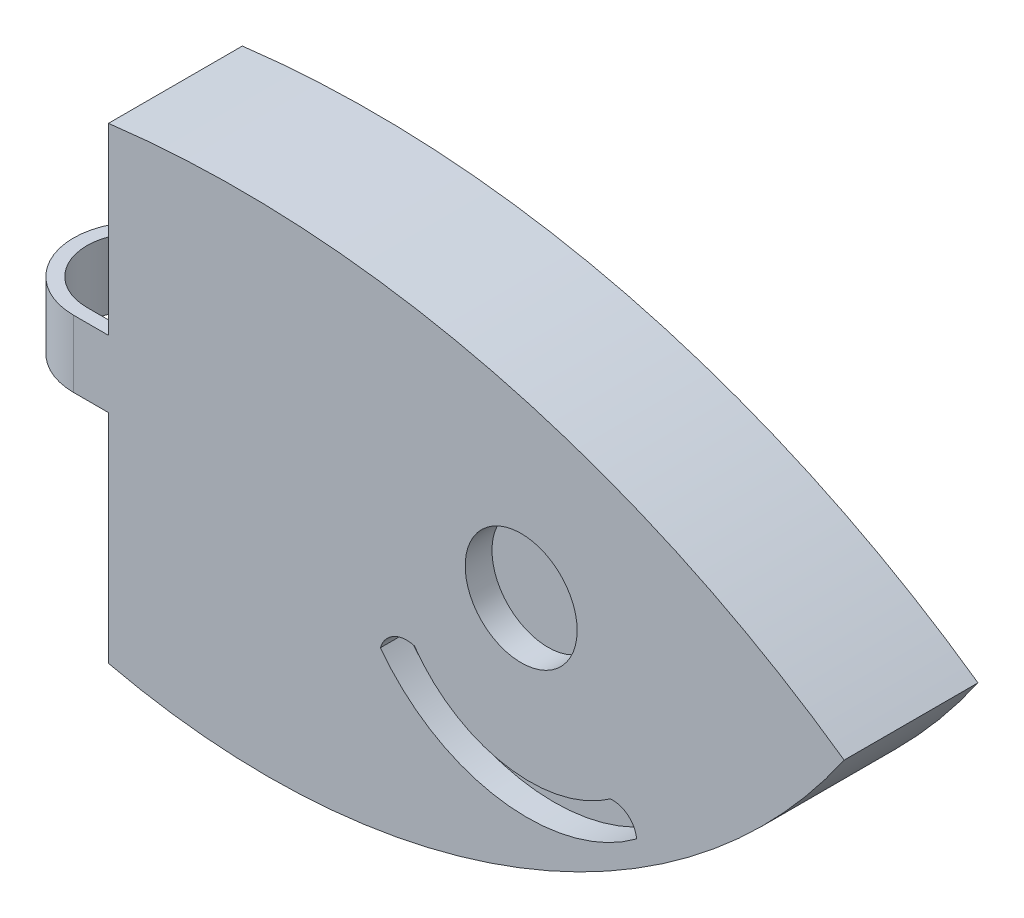
SolidWorks part; units mm, degrees
ref_plane "前基準面" through (0, 0, 0) normal (0, 0, 1) x (1, 0, 0)
ref_plane "上基準面" through (0, 0, 0) normal (0, 1, 0) x (1, 0, 0)
ref_plane "右基準面" through (0, 0, 0) normal (1, 0, 0) x (0, 0, -1)
sketch "草圖1" plane through (0, 0, 0) normal (0, 0, 1) x (1, 0, 0)
  line L0 (-54.9695, 13.7192) -> (-54.9695, -21.2248)
  arc A0 (0, 0) -> (-54.9695, 13.7192) centre (-45.209, -64.1571) ccw
  arc A1 (0, 0) -> (-54.9695, -21.2248) centre (-43.0701, 29.7516) cw
  point P6 (-54.9695, -21.2248)
extrude "填料-伸長1" add sketch "草圖1" along normal blind 10 contours A0 L0 A1
sketch "草圖2" plane through (-3.5989, 0, 10) normal (0, 0, 1) x (1, 0, 0)
  circle A0 centre (-20.5341, -1.5858) radius 4.1827
extrude "除料-伸長1" cut sketch "草圖2" against normal blind 2
sketch "草圖3" plane through (-4.4987, 1.8692, 10) normal (0, 0, 1) x (1, 0, 0)
  arc A0 (-30.1543, -11.9278) -> (-11.0071, -14.7229) centre (-19.1831, -3.7517) ccw
  arc A1 (-27.6167, -10.5308) -> (-12.9679, -13.1163) centre (-18.9996, -4.4991) ccw
  arc A2 (-27.6167, -10.5308) -> (-30.1543, -11.9278) centre (-28.187, -12.4981) ccw
  arc A3 (-12.9679, -13.1163) -> (-11.0071, -14.7229) centre (-12.7908, -14.9) cw
extrude "除料-伸長2" cut sketch "草圖3" against normal blind 2
sketch "草圖4" plane through (0, 0, 0) normal (0, 1, 0) x (1, 0, 0)
  line L0 (-54.9695, 0) -> (-57.5782, 0)
  line L1 (-54.9695, -10) -> (-57.5782, -10)
  line L2 (-54.9695, 0) -> (-54.9695, -10)
  arc A0 (-57.5782, 0) -> (-57.5782, -10) centre (-57.5782, -5) ccw
extrude "填料-伸長2" add sketch "草圖4" against normal blind 5 contours A0 L1 L2 L0
sketch "草圖5" plane through (0, 0, 0) normal (0, 1, 0) x (1, 0, 0)
  line L0 (-56.2739, 0) -> (-56.2739, -1)
  line L1 (-54.9695, 0) -> (-57.5782, 0) construction
  line L2 (-55.8781, -10) -> (-55.8781, -9)
  line L3 (-54.9695, -10) -> (-57.5782, -10) construction
  line L4 (-54.9695, -1) -> (-57.5782, -1)
  line L5 (-54.9695, 0) -> (-54.9695, -10) construction
  line L6 (-54.9695, -9) -> (-57.5782, -9)
  line L7 (-54.9695, -1) -> (-54.9695, -9)
  arc A0 (-57.5782, -1) -> (-57.5782, -9) centre (-57.5782, -5) ccw
extrude "除料-伸長4" cut sketch "草圖5" against normal blind 5 contours A0 L6 L7 L4
